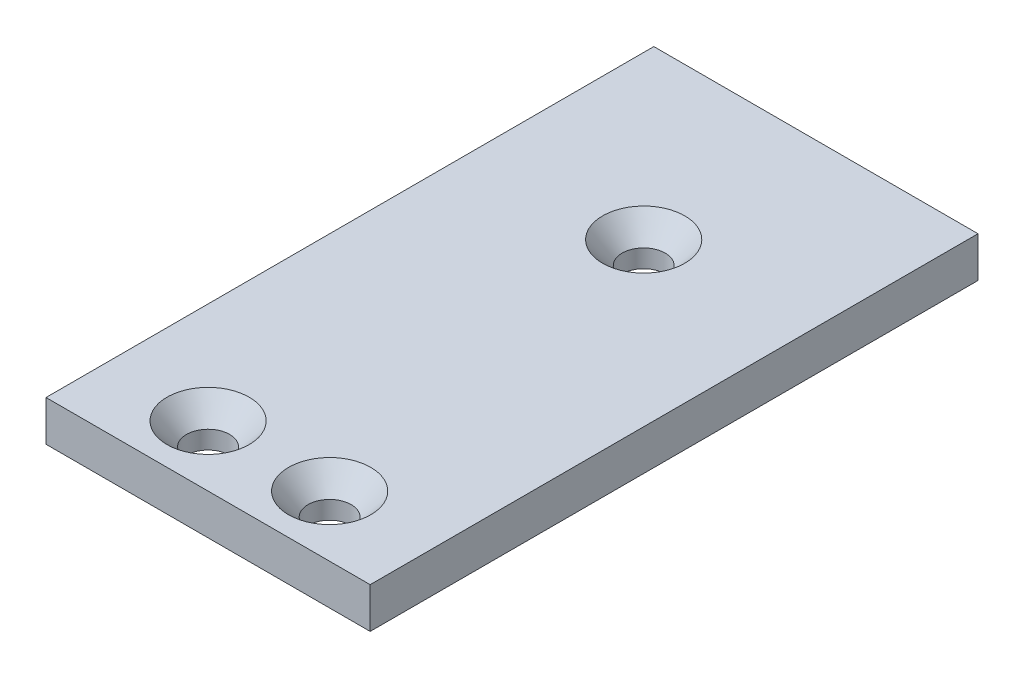
SolidWorks part; units mm, degrees
material "6061 Alloy"
ref_plane "Front Plane" through (0, 0, 0) normal (0, 0, 1) x (1, 0, 0)
ref_plane "Top Plane" through (0, 0, 0) normal (0, 1, 0) x (1, 0, 0)
ref_plane "Right Plane" through (0, 0, 0) normal (1, 0, 0) x (0, 0, -1)
sketch "Sketch1" plane through (0, 0, 0) normal (0, 1, 0) x (1, 0, 0)
  line L1 (0, 0) -> (50.8, 0)
  line L2 (0, 0) -> (0, 95.25)
  line L3 (0, 95.25) -> (50.8, 95.25)
  line L4 (50.8, 0) -> (50.8, 95.25)
  dimension "D1" = 50.8
  dimension "D2" = 95.25
extrude "Boss-Extrude1" add sketch "Sketch1" along normal blind 6.35
hole_wizard "CSK for 1/4 Flat Head Machine Screw1" positions "Sketch2" profile "Sketch4" countersink size "1/4" standard "ANSI Inch" end condition through all
sketch "Sketch2" plane through (0, 6.35, 0) normal (0, 1, 0) x (1, 0, 0)
  line L0 (50.8, 95.25) -> (0, 95.25) construction
  line L1 (0, 0) -> (50.8, 0) construction
  line L2 (50.8, 0) -> (50.8, 95.25) construction
  line L3 (0, 95.25) -> (0, 0) construction
  line L4 (25.4, 95.25) -> (25.4, 0) construction
  point P0 (25.4, 68.2625)
  point P2 (15.875, 9.525)
  point P4 (34.925, 9.525)
  dimension "D1" = 26.9875
  dimension "D2" = 9.525
  dimension "D3" = 9.525
  dimension "D4" = 15.875
  dimension "D5" = 15.875
sketch "Sketch4" plane through (25.4, 6.35, -68.2625) normal (1, 0, 0) x (0, 0, 1)
  line L0 (0, 0) -> (0, 6.35)
  line L1 (0, 6.35) -> (3.3782, 6.35)
  line L2 (3.3782, 6.35) -> (3.3782, 3.5209)
  line L3 (3.3782, 3.5209) -> (6.4389, 0)
  line L5 (6.4389, 0) -> (0, 0)
  line L6 (-3.3782, 3.5209) -> (-6.4389, 0) construction
  line L11 (0, -6.35) -> (0, 107.95) construction
  dimension "Thru Hole Dia." = 6.7564
  dimension "Thru Hole Depth" = 6.35
  dimension "Near C'Sink Dia." = 12.8778
  dimension "Near C'Sink Angle" = 82
